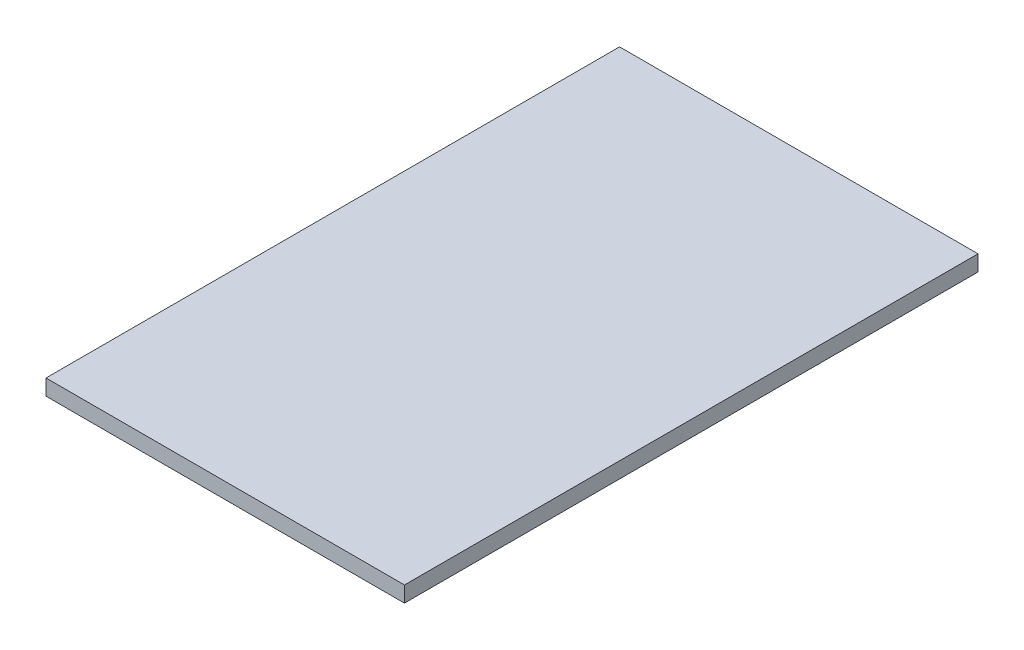
SolidWorks part; units mm, degrees
ref_plane "Front Plane" through (0, 0, 0) normal (0, 0, 1) x (1, 0, 0)
ref_plane "Top Plane" through (0, 0, 0) normal (0, 1, 0) x (1, 0, 0)
ref_plane "Right Plane" through (0, 0, 0) normal (1, 0, 0) x (0, 0, -1)
other "Default"
sketch "Sketch1" plane through (0, 0, 0) normal (0, 1, 0) x (1, 0, 0)
  line L1 (-25, -40) -> (25, -40)
  line L2 (-25, -40) -> (-25, 40)
  line L3 (-25, 40) -> (25, 40)
  line L4 (25, -40) -> (25, 40)
  line L5 (-25, -40) -> (25, 40) construction
  line L6 (-25, 40) -> (25, -40) construction
  point P0 (0, 0)
  dimension "Width" = 80
  dimension "Length" = 50
extrude "Boss-Extrude1" add sketch "Sketch1" along normal mid plane 2.2
